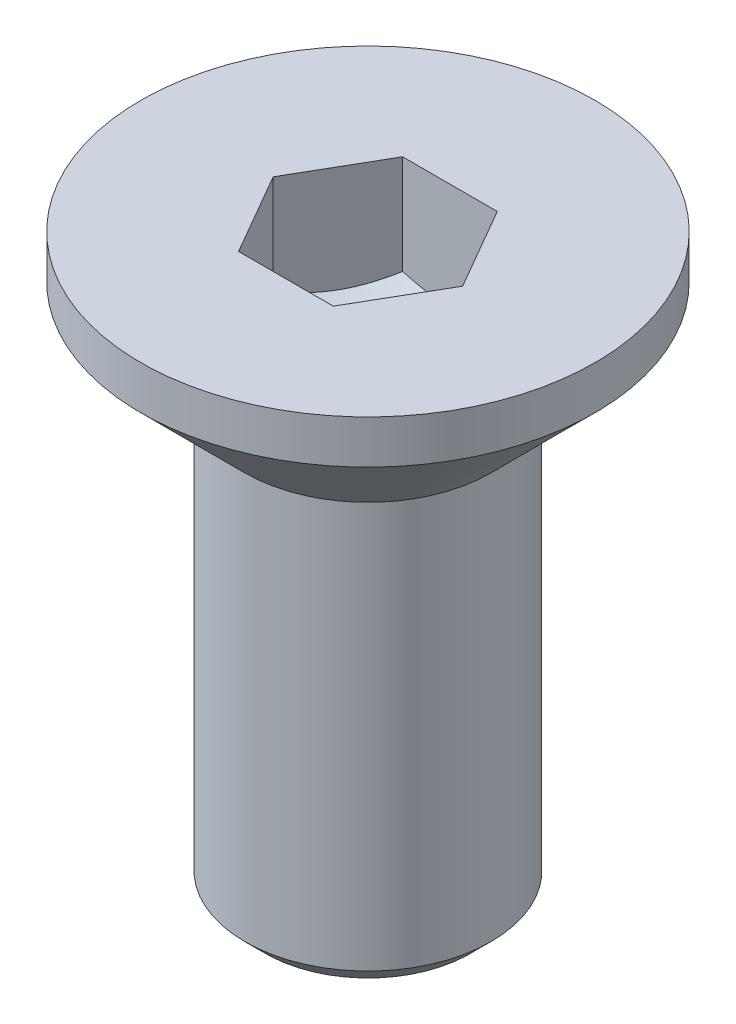
SolidWorks part; units mm, degrees
material "AISI 304"
ref_plane "前视基准面" through (0, 0, 0) normal (0, 0, 1) x (1, 0, 0)
ref_plane "上视基准面" through (0, 0, 0) normal (0, 1, 0) x (1, 0, 0)
ref_plane "右视基准面" through (0, 0, 0) normal (1, 0, 0) x (0, 0, -1)
sketch "草图1" plane through (0, 0, 0) normal (0, 0, 1) x (1, 0, 0)
  line L0 (1.5, -1.8) -> (1.5, -6.75)
  line L1 (1.5, -6.75) -> (1.25, -7)
  line L2 (1.25, -7) -> (0, -7)
  line L3 (0, -7) -> (0, -1.8774)
  line L4 (0, -1.8774) -> (1, -1.3)
  line L5 (1, -1.3) -> (1, 0)
  line L6 (1, 0) -> (2.77, 0)
  line L7 (2.77, 0) -> (2.77, -0.53)
  line L8 (2.77, -0.53) -> (1.5, -1.8)
  line L9 (0, 0) -> (0, 16054.5247) construction
  dimension "D1" = 60
  dimension "d" = 3
  dimension "ad" = 45
  dimension "dk" = 5.54
  dimension "k" = 1.8
  dimension "D2" = 45
  dimension "w" = 0.5
  dimension "s" = 2
  dimension "D3" = 7
  dimension "D4" = 2.5
revolve "旋转1" add sketch "草图1" angle 360 about L9
sketch "草图2" plane through (0, 0, 0) normal (0, 1, 0) x (1, 0, 0)
  line L1 (1.1547, 0) -> (0.5774, 1)
  line L2 (0.5774, 1) -> (-0.5774, 1)
  line L3 (-0.5774, 1) -> (-1.1547, 0)
  line L4 (-1.1547, 0) -> (-0.5774, -1)
  line L5 (-0.5774, -1) -> (0.5774, -1)
  line L6 (0.5774, -1) -> (1.1547, 0)
  circle A0 centre (0, 0) radius 1 construction
  circle A1 centre (0, 0) radius 1 construction
extrude "切除-拉伸1" cut sketch "草图2" against normal up to surface (1.2107 mm away)
